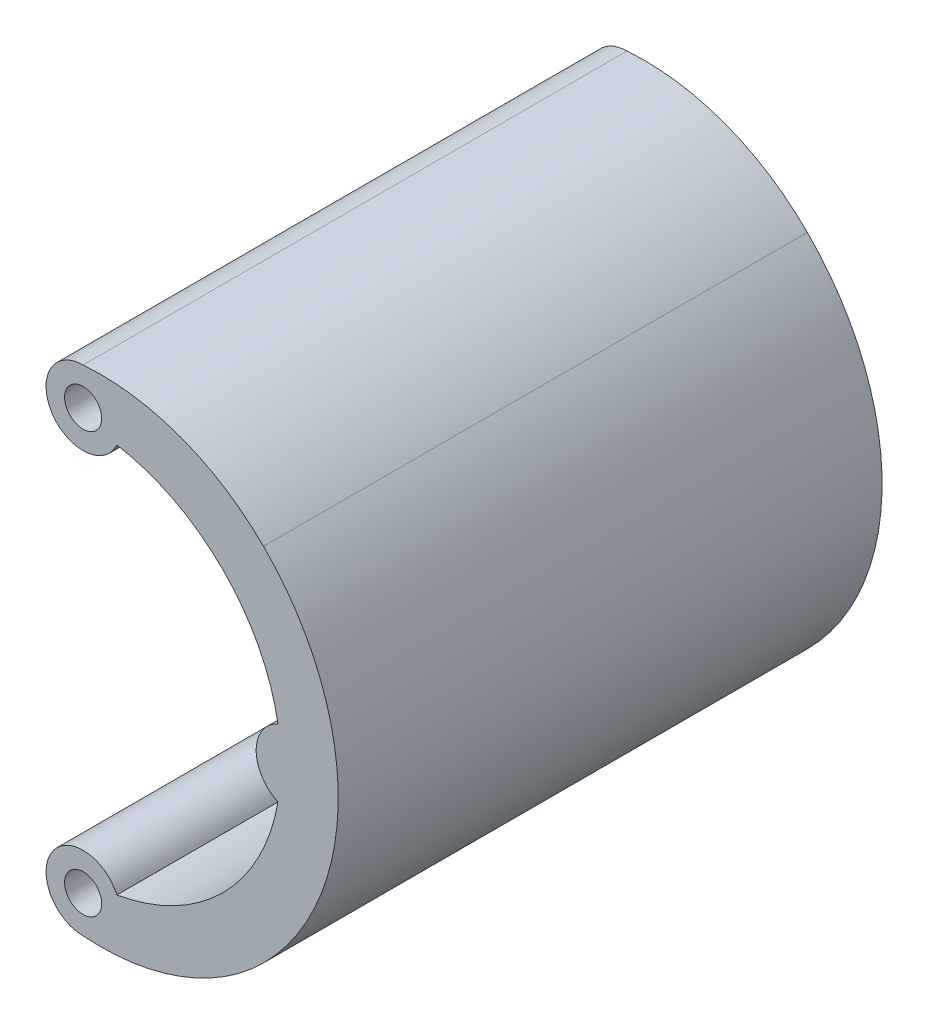
SolidWorks part; units mm, degrees
material "TPU 95A"
ref_plane "Front Plane" through (0, 0, 0) normal (1, 0, 0) x (0, 1, 0)
ref_plane "Top Plane" through (0, 0, 0) normal (0, 0, 1) x (0, 1, 0)
ref_plane "Right Plane" through (0, 0, 0) normal (0, 1, 0) x (-1, 0, 0)
sketch "Sketch1" plane through (0, 0, 0) normal (0, 0, 1) x (0, 1, 0)
  line L0 (0, -17) -> (0, 17) construction
  line L1 (-17, 0) -> (17, 0) construction
  line L2 (0, 0) -> (1.4142, 1.4142) construction
  line L3 (0, 0) -> (-1.4142, -1.4142) construction
  line L4 (0, 0) -> (-1.4142, -1.4142) construction
  line L5 (0, 0) -> (1.4142, -1.4142) construction
  circle A0 centre (0, 17) radius 3
  circle A1 centre (0, -17) radius 3
  circle A2 centre (-17, 0) radius 3
  circle A3 centre (17, 0) radius 3
  arc A4 (15.7647, -2.7339) -> (2.7339, -15.7647) centre (0, 0) cw
  arc A5 (0, -20) -> (20, 0) centre (1.4142, -1.4142) ccw
  arc A6 (-20, 0) -> (0, -20) centre (-1.4142, -1.4142) ccw
  arc A7 (-2.7339, -15.7647) -> (-15.7647, -2.7339) centre (0, 0) cw
  circle A8 centre (0, 0) radius 13.75 construction
  arc A9 (-14.5943, -14.5943) -> (14.5943, -14.5943) centre (0, 0) ccw
  point P4 (0, 0)
  point P8 (0, 0)
  dimension "D3" = 6
  dimension "D4" = 6
  dimension "D5" = 2
  dimension "D6" = 45
  dimension "D7" = 16
  dimension "D8" = 2
  dimension "D9" = 27.5
  dimension "D11" = 90
  dimension "D1" = 34
  dimension "D2" = 34
  dimension "D10" = 2
extrude "Boss-Extrude1" add sketch "Sketch1" along normal blind 44
hole_wizard "Ø3.0mm Dowel Hole1" positions "Sketch3" profile "Sketch5" hole size "Ø3.0" standard "ANSI Metric" end condition through all
sketch "Sketch3" plane through (0, 0, 0) normal (0, 0, 1) x (1, 0, 0)
  point P0 (0, 17)
  point P3 (0, -17)
sketch "Sketch5" plane through (0, 17, 0) normal (1, 0, 0) x (0, 1, 0)
  line L0 (0, 0) -> (0, 44)
  line L1 (0, 44) -> (1.5, 44)
  line L2 (1.5, 44) -> (1.5, 0.021)
  line L3 (1.5, 0.021) -> (1.525, 0)
  line L5 (1.525, 0) -> (0, 0)
  line L6 (-1.5, 0.021) -> (-1.525, 0) construction
  line L11 (0, -6.35) -> (0, 107.95) construction
  dimension "Thru Hole Dia." = 3
  dimension "Thru Hole Depth" = 44
  dimension "Near C'Sink Dia." = 3.05
  dimension "Near C'Sink Angle" = 100
sketch "Sketch7" plane through (0, 0, 0) normal (0, 0, -1) x (1, 0, 0)
  circle A0 centre (-17, 0) radius 1.715
  circle A1 centre (17, 0) radius 1.715
  dimension "D1" = 3.43
extrude "Cut-Extrude2" [suppressed] cut sketch "Sketch7" against normal blind 5
equation "\"Alum Bracket Thickness\"= 0.35in"
equation "\"D1@Boss-Extrude1\"=35"
equation "\"spur gear gap\"= 0.094in"
